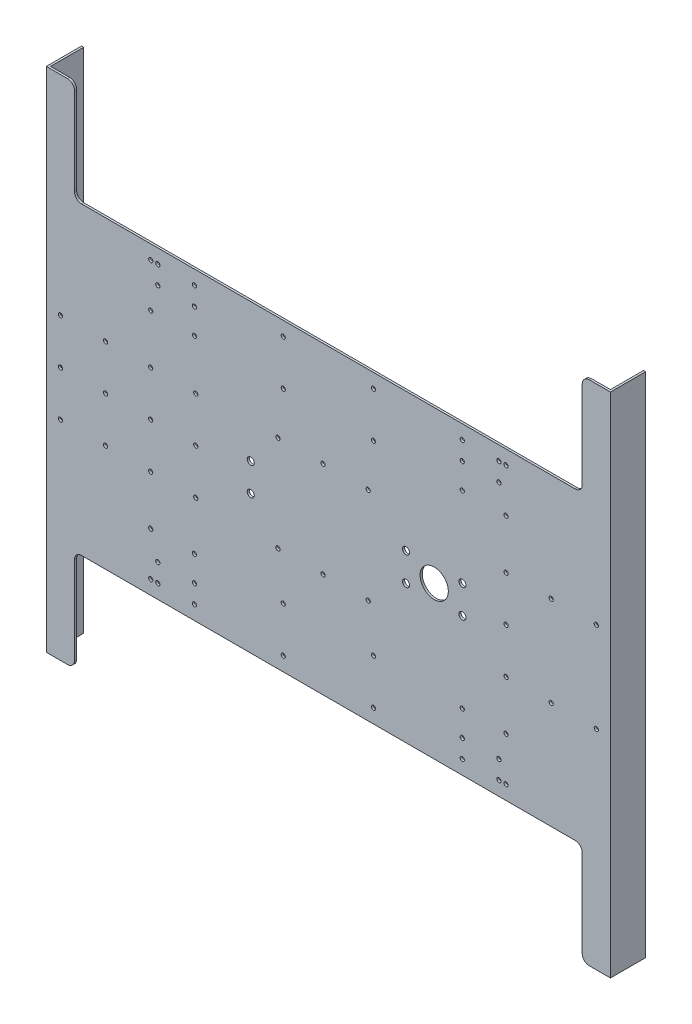
SolidWorks part; units mm, degrees
ref_plane "前视基准面" through (0, 0, 0) normal (0, 0, 1) x (1, 0, 0)
ref_plane "上视基准面" through (0, 0, 0) normal (0, 1, 0) x (1, 0, 0)
ref_plane "右视基准面" through (0, 0, 0) normal (1, 0, 0) x (0, 0, -1)
sketch "草图1" plane through (0, 0, 0) normal (0, 0, 1) x (1, 0, 0)
  line L14 (125, 180) -> (125, -180)
  line L15 (-56.8795, 0) -> (-49.6653, 0) construction
  line L16 (-275.16, 180) -> (-273.66, 180)
  line L17 (-275.16, -180) -> (-273.66, -180)
  line L18 (-275.16, 180) -> (-275.16, -180)
  line L19 (-260.16, 180) -> (-273.66, 180)
  line L20 (-267.66, -180) -> (-273.66, -180)
  line L21 (-255.16, 175) -> (-255.16, 113)
  line L22 (-255.16, -167.5) -> (-255.16, -120.5)
  line L23 (-255.16, 167.5) -> (-255.16, 175)
  line L24 (-275.16, -180) -> (-273.66, -180)
  line L25 (-260.16, -180) -> (-273.66, -180)
  line L26 (-255.16, -167.5) -> (-255.16, -113)
  line L27 (-255.16, -167.5) -> (-255.16, -175)
  line L28 (-250.16, -108) -> (100, -108)
  line L29 (-250.16, 108) -> (100, 108)
  line L30 (125, -180) -> (123.5, -180)
  line L31 (125, 180) -> (125, -180)
  line L32 (125, 180) -> (123.5, 180)
  line L33 (117.5, -180) -> (123.5, -180)
  line L34 (110, 180) -> (123.5, 180)
  line L35 (105, -167.5) -> (105, -113)
  line L36 (92.5, 108) -> (100, 108)
  line L37 (105, 113) -> (105, 175)
  line L38 (125, -180) -> (123.5, -180)
  line L39 (110, -180) -> (123.5, -180)
  line L40 (105, -113) -> (105, -175)
  line L41 (-277.7452, 0) -> (135.479, 0) construction
  line L42 (0, 0) -> (-20, 0)
  line L43 (-75.08, -108) -> (-75.08, 108)
  line L44 (-277.7452, 0) -> (135.479, 0) construction
  circle A33 centre (-201.08, 98) radius 1.5
  circle A34 centre (-170.08, 98) radius 1.5
  arc A35 (-255.16, 113) -> (-250.16, 108) centre (-250.16, 113) ccw
  arc A36 (-250.16, -108) -> (-255.16, -113) centre (-250.16, -113) ccw
  arc A37 (-255.16, 175) -> (-260.16, 180) centre (-260.16, 175) ccw
  arc A38 (-260.16, -180) -> (-255.16, -175) centre (-260.16, -175) ccw
  arc A39 (100, 108) -> (105, 113) centre (100, 113) ccw
  arc A40 (110, 180) -> (105, 175) centre (110, 175) ccw
  arc A41 (105, -175) -> (110, -180) centre (110, -175) ccw
  arc A42 (105, -113) -> (100, -108) centre (100, -113) ccw
  circle A43 centre (0, 0) radius 10
  circle A44 centre (115, 32) radius 1.5
  circle A45 centre (83, 32) radius 1.5
  circle A46 centre (19.92, 98) radius 1.5
  circle A47 centre (50.92, 98) radius 1.5
  circle A48 centre (19.92, 67) radius 1.5
  circle A49 centre (50.92, 67) radius 1.5
  circle A50 centre (-201.08, -98) radius 1.5
  circle A51 centre (-170.08, -98) radius 1.5
  circle A52 centre (19.92, -98) radius 1.5
  circle A53 centre (50.92, -98) radius 1.5
  circle A54 centre (115, -32) radius 1.5
  circle A55 centre (83, -32) radius 1.5
  circle A56 centre (-107.08, 98) radius 1.5
  circle A57 centre (-107.08, 66) radius 1.5
  circle A58 centre (-43.08, 98) radius 1.5
  circle A59 centre (-43.08, 66) radius 1.5
  circle A60 centre (-107.08, -98) radius 1.5
  circle A61 centre (-107.08, -66) radius 1.5
  circle A62 centre (-43.08, -98) radius 1.5
  circle A63 centre (-43.08, -66) radius 1.5
  circle A64 centre (-201.08, 67) radius 1.5
  circle A65 centre (-170.08, 67) radius 1.5
  circle A66 centre (-201.08, -67) radius 1.5
  circle A67 centre (-170.08, -67) radius 1.5
  circle A68 centre (19.92, 67) radius 1.5
  circle A69 centre (50.92, 67) radius 1.5
  circle A70 centre (19.92, -67) radius 1.5
  circle A71 centre (50.92, -67) radius 1.5
  circle A72 centre (19.92, -67) radius 1.5
  circle A73 centre (50.92, -67) radius 1.5
  circle A74 centre (-196.08, 98) radius 1.5
  circle A75 centre (-170.08, 98) radius 1.5
  circle A76 centre (-196.08, 85) radius 1.5
  circle A77 centre (-170.08, 85) radius 1.5
  circle A78 centre (19.92, 98) radius 1.5
  circle A79 centre (45.92, 98) radius 1.5
  circle A80 centre (19.92, 85) radius 1.5
  circle A81 centre (45.92, 85) radius 1.5
  circle A82 centre (-196.08, -98) radius 1.5
  circle A83 centre (-170.08, -98) radius 1.5
  circle A84 centre (-196.08, -85) radius 1.5
  circle A85 centre (-170.08, -85) radius 1.5
  circle A86 centre (19.92, -98) radius 1.5
  circle A87 centre (45.92, -98) radius 1.5
  circle A88 centre (19.92, -85) radius 1.5
  circle A89 centre (45.92, -85) radius 1.5
  circle A90 centre (-20, 10) radius 2.5
  circle A91 centre (-20, -10) radius 2.5
  circle A92 centre (20, 10) radius 2.5
  circle A93 centre (20, -10) radius 2.5
  circle A94 centre (-265.16, 32) radius 1.5
  circle A95 centre (-233.16, 32) radius 1.5
  circle A96 centre (-201.16, 32) radius 1.5
  circle A97 centre (-201.16, 0) radius 1.5
  circle A98 centre (-265.16, -32) radius 1.5
  circle A99 centre (-233.16, -32) radius 1.5
  circle A100 centre (-201.16, -32) radius 1.5
  circle A101 centre (-130.16, 10) radius 2.5
  circle A102 centre (-130.16, -10) radius 2.5
  circle A103 centre (-169.16, 32) radius 1.5
  circle A104 centre (-169.16, 0) radius 1.5
  circle A105 centre (-169.16, -32) radius 1.5
  circle A106 centre (-265.16, 0) radius 1.5
  circle A107 centre (-233.16, 0) radius 1.5
  circle A108 centre (51, 32) radius 1.5
  circle A109 centre (51, 0) radius 1.5
  circle A110 centre (51, -32) radius 1.5
  circle A111 centre (-110.83, 34) radius 1.5
  circle A112 centre (-78.83, 34) radius 1.5
  circle A113 centre (-46.83, 34) radius 1.5
  circle A114 centre (-110.83, -34) radius 1.5
  circle A115 centre (-78.83, -34) radius 1.5
  circle A116 centre (-46.83, -34) radius 1.5
  dimension "D1" = 360
extrude "凸台-拉伸1" add sketch "草图1" along normal blind 1.5 contours A42 L35 L40 A41 L39 L33 L30 L14 L32 L34 A40 L37 A39 L29 L43 L28 A116 A113 A110 A109 A108 A93 A92 A91 A90 A89 A88 A87 A81 A80 A79 A71 A70 | L25 A38 L27 L22 L26 A36 L28 L43 L29 A35 L21 A37 L19 L16 L18 L17 L20 A115 A114 A112 A111 A107 A106 A105 A104 A103 A102 A101 A100 A99 A98 A97 A96
sketch "草图2" plane through (0, 0, 1.5) normal (0, 0, 1) x (1, 0, 0)
  line L0 (110, -180) -> (125, -180) construction
  line L1 (125, 180) -> (123.5, 180)
  line L2 (125, 180) -> (125, -180)
  line L3 (125, -180) -> (123.5, -180)
  line L4 (123.5, 180) -> (123.5, -180)
  line L5 (-267.66, -180) -> (-273.66, -180) construction
  line L6 (-275.16, 180) -> (-273.66, 180)
  line L7 (-275.16, 180) -> (-275.16, -180)
  line L8 (-275.16, -180) -> (-273.66, -180)
  line L9 (-273.66, 180) -> (-273.66, -180)
  dimension "D1" = 1.5
  dimension "D2" = 1.5
extrude "凸台-拉伸2" add sketch "草图2" against normal blind 25
